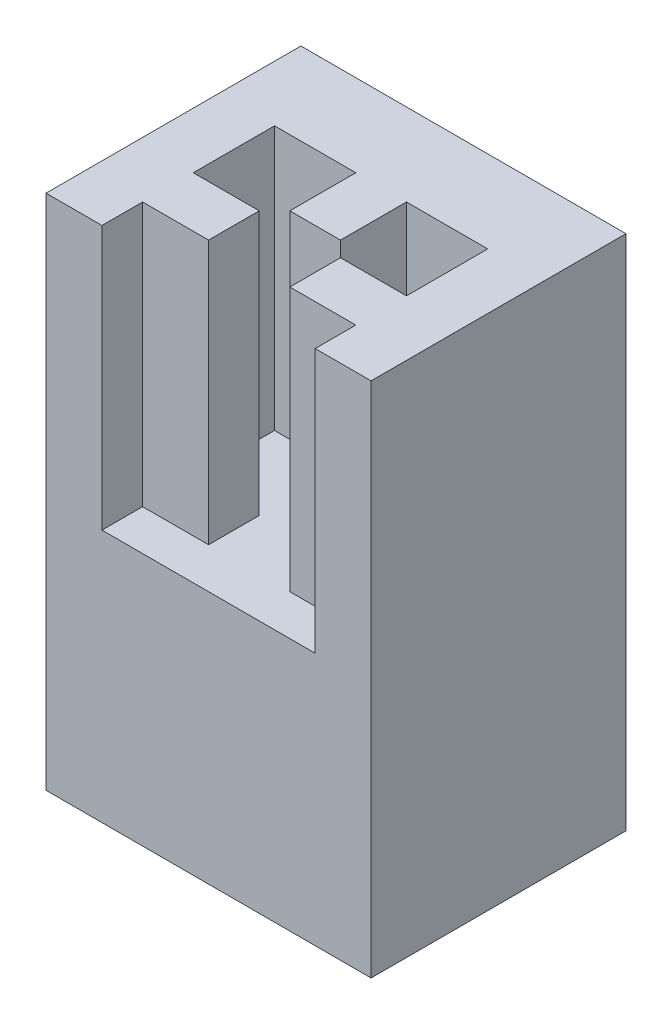
SolidWorks part; units mm, degrees
ref_plane "Plan de face" through (0, 0, 0) normal (0, 0, 1) x (1, 0, 0)
ref_plane "Plan de dessus" through (0, 0, 0) normal (0, 1, 0) x (1, 0, 0)
ref_plane "Plan de droite" through (0, 0, 0) normal (1, 0, 0) x (0, 0, -1)
sketch "Esquisse1" plane through (0, 0, 0) normal (0, 1, 0) x (1, 0, 0)
  line L1 (-39.5605, 3.8269) -> (-8.7605, 3.8269)
  line L2 (-39.5605, 3.8269) -> (-39.5605, -20.3231)
  line L3 (-39.5605, -20.3231) -> (-8.7605, -20.3231)
  line L4 (-8.7605, 3.8269) -> (-8.7605, -20.3231)
  line L5 (-39.5605, 3.8269) -> (-8.7605, -20.3231) construction
  line L6 (-39.5605, -20.3231) -> (-8.7605, 3.8269) construction
  point P0 (-24.1605, -8.2481)
  dimension "D1" = 30.8
  dimension "D2" = 24.15
extrude "Boss.-Extru.1" add sketch "Esquisse1" along normal blind 49
sketch "Esquisse3" plane through (0, 0, 0) normal (0, -1, 0) x (-1, 0, 0)
  line L0 (39.5605, 3.8269) -> (39.5605, -20.3231) construction
  line L3 (39.5605, -20.3231) -> (8.7605, -20.3231) construction
  circle A0 centre (24.1605, -8.3231) radius 7.5
  dimension "D1" = 15
  dimension "D2" = 15.4
  dimension "D3" = 12
extrude "Enlèv. mat.-Extru.3" cut sketch "Esquisse3" against normal blind 18
sketch "Esquisse4" plane through (0, 49, 0) normal (0, 1, 0) x (1, 0, 0)
  line L0 (-34.2605, -20.3231) -> (-34.2605, -16.4731)
  line L1 (-39.5605, -20.3231) -> (-8.7605, -20.3231) construction
  line L2 (-34.2605, -16.4731) -> (-28.0105, -16.4731)
  line L3 (-28.0105, -16.4731) -> (-28.0105, -11.6731)
  line L4 (-28.0105, -11.6731) -> (-34.2605, -11.6731)
  line L5 (-34.2605, -11.6731) -> (-34.2605, -3.9731)
  line L6 (-34.2605, -3.9731) -> (-26.5605, -3.9731)
  line L7 (-26.5605, -3.9731) -> (-26.5605, -10.2231)
  line L8 (-26.5605, -10.2231) -> (-21.7605, -10.2231)
  line L9 (-21.7605, -10.2231) -> (-21.7605, -3.9731)
  line L10 (-21.7605, -3.9731) -> (-14.0605, -3.9731)
  line L11 (-14.0605, -3.9731) -> (-14.0605, -11.6731)
  line L12 (-14.0605, -11.6731) -> (-20.3105, -11.6731)
  line L13 (-20.3105, -11.6731) -> (-20.3105, -16.4731)
  line L14 (-20.3105, -16.4731) -> (-14.0605, -16.4731)
  line L15 (-14.0605, -16.4731) -> (-14.0605, -20.3231)
  line L16 (-39.5605, 3.8269) -> (-39.5605, -20.3231) construction
  dimension "D1" = 5.3
  dimension "D2" = 3.85
  dimension "D3" = 6.25
  dimension "D4" = 4.8
  dimension "D5" = 6.25
  dimension "D6" = 7.7
  dimension "D7" = 7.7
  dimension "D8" = 6.25
  dimension "D9" = 4.8
  dimension "D10" = 6.25
  dimension "D11" = 7.7
  dimension "D12" = 7.7
  dimension "D13" = 6.25
  dimension "D14" = 4.8
  dimension "D15" = 6.25
extrude "Enlèv. mat.-Extru.4" cut sketch "Esquisse4" against normal blind 25 and the other way through all flip side to cut
